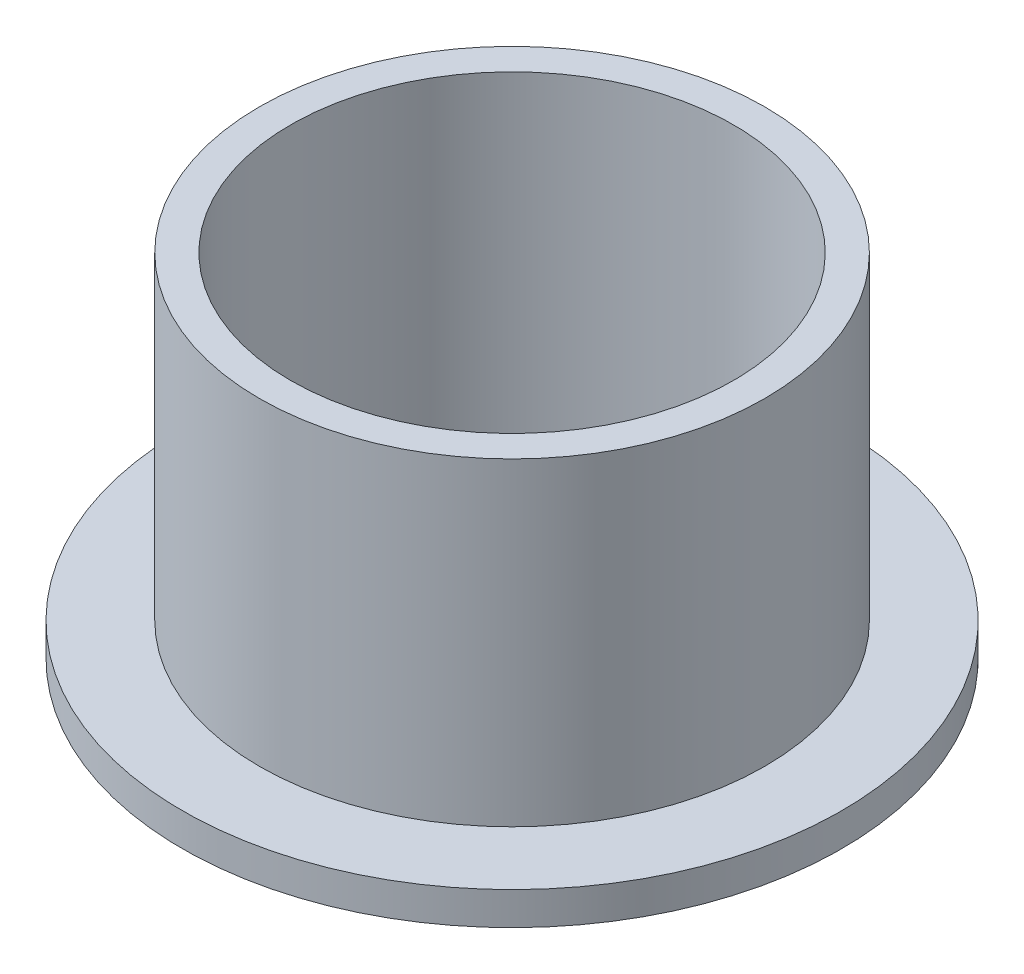
SolidWorks part; units mm, degrees
ref_plane "Front" through (0, 0, 0) normal (0, 0, 1) x (1, 0, 0)
ref_plane "Top" through (0, 0, 0) normal (0, 1, 0) x (1, 0, 0)
ref_plane "Right" through (0, 0, 0) normal (1, 0, 0) x (0, 0, -1)
sketch "Sketch1" plane through (0, 0, 0) normal (0, 1, 0) x (1, 0, 0)
  circle A0 centre (0, 0) radius 8.001
  circle A1 centre (0, 0) radius 9.1281
  circle A2 centre (0, 0) radius 11.9062
  dimension "ID" = 16.002
  dimension "OD" = 18.2562
  dimension "FlangeOD" = 23.8125
sketch "Sketch2" plane through (0, 0, 0) normal (0, 1, 0) x (1, 0, 0)
  circle A0 centre (0, 0) radius 8.001 construction
  circle A1 centre (0, 0) radius 9.1281 construction
  circle A2 centre (0, 0) radius 8.001
  circle A3 centre (0, 0) radius 9.1281
extrude "Boss-Extrude1" add sketch "Sketch2" along normal blind 12.7
sketch "Sketch3" plane through (0, 0, 0) normal (0, 1, 0) x (1, 0, 0)
  circle A0 centre (0, 0) radius 11.9062 construction
  circle A1 centre (0, 0) radius 9.1281 construction
  circle A2 centre (0, 0) radius 11.9062
  circle A3 centre (0, 0) radius 9.1281
extrude "Boss-Extrude2" add sketch "Sketch3" along normal blind 1.1906
